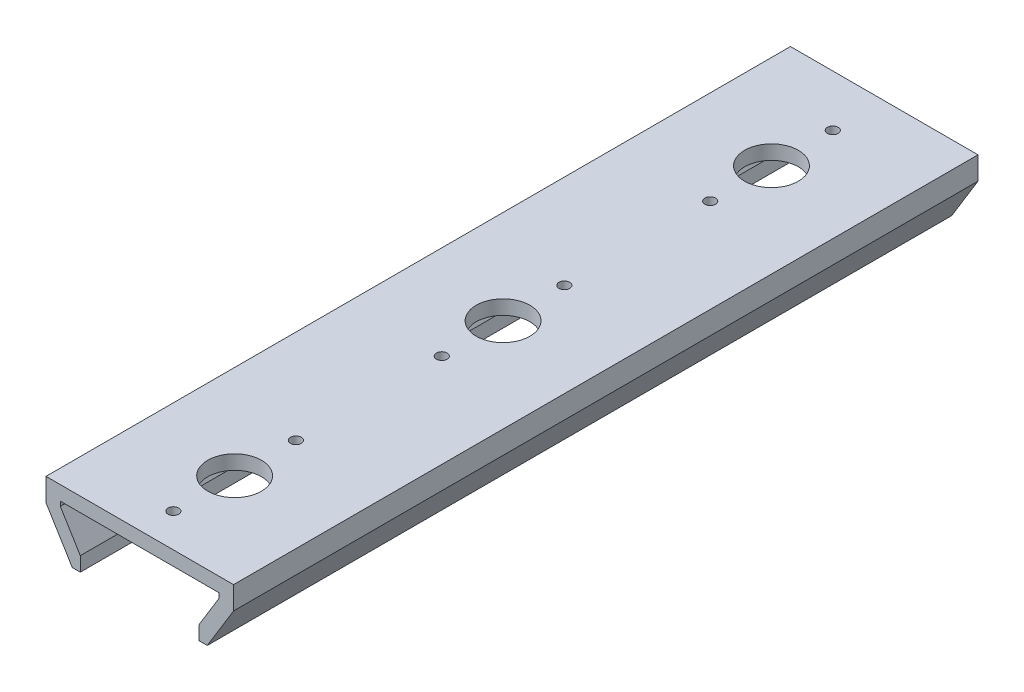
SolidWorks part; units mm, degrees
ref_plane "Płaszczyzna przednia" through (0, 0, 0) normal (0, 0, 1) x (1, 0, 0)
ref_plane "Płaszczyzna górna" through (0, 0, 0) normal (0, 1, 0) x (1, 0, 0)
ref_plane "Płaszczyzna prawa" through (0, 0, 0) normal (1, 0, 0) x (0, 0, -1)
sketch "Sketch1" plane through (0, 0, 0) normal (0, 0, 1) x (1, 0, 0)
  line L0 (0, -13.2894) -> (0, -81.2091) construction
  line L1 (0, -13.4894) -> (22, -13.4894)
  line L2 (22, -13.4894) -> (22, -14.4894)
  line L3 (16.5, -23.4894) -> (0, -23.4894)
  line L4 (22, -14.4894) -> (16.5, -23.4894)
  line L5 (0, -13.4894) -> (0, -23.4894)
  line L6 (0, -13.2894) -> (22.2, -13.2894)
  line L7 (22.2, -13.2894) -> (22.2, -14.5456)
  line L8 (22.2, -14.5456) -> (16.6122, -23.6894)
  line L9 (16.6122, -23.6894) -> (0, -23.6894)
  line L11 (18.8555, -27.6894) -> (16.6122, -27.6894)
  line L13 (-26.2, -9.2894) -> (26.2, -9.2894)
  line L14 (26.2, -9.2894) -> (26.2, -15.6711)
  line L15 (26.2, -15.6711) -> (18.8555, -27.6894)
  line L16 (0, -13.2894) -> (0, -31.461)
  line L17 (16.6122, -23.6894) -> (16.6122, -27.6894)
  line L18 (-4.2, -9.2894) -> (-4.2, -27.6894) construction
  line L20 (-4.2, -9.2894) -> (26.2, -9.2894) construction
  line L21 (18.8555, -27.6894) -> (-4.2, -27.6894) construction
  line L22 (-0.2, -13.2894) -> (-0.2, -23.6894) construction
  line L23 (16.6122, -23.6894) -> (-0.2, -23.6894) construction
  line L24 (-0.2, -13.2894) -> (22.2, -13.2894) construction
  line L25 (-26.2, -9.2894) -> (-26.2, -15.6711)
  line L26 (-26.2, -15.6711) -> (-18.8555, -27.6894)
  line L27 (-18.8555, -27.6894) -> (-16.6122, -27.6894)
  line L28 (-16.6122, -23.6894) -> (-16.6122, -27.6894)
  line L29 (-22.2, -14.5456) -> (-16.6122, -23.6894)
  line L30 (-22.2, -13.2894) -> (-22.2, -14.5456)
  line L31 (0, -13.2894) -> (-22.2, -13.2894)
  point P4 (22, -23.4894)
  dimension "D1" = 9
  dimension "D2" = 5.5
  dimension "D3" = 10
  dimension "D4" = 22
  dimension "D5" = 0.2
  dimension "D6" = 4
extrude "Boss-Extrude1" add sketch "Sketch1" along normal blind 213 contours L31 L6 L7 L8 L17 L11 L15 L14 L13 L25 L26 L27 L28 L29 L30
sketch "Sketch2" plane through (0, -9.2894, 0) normal (0, 1, 0) x (1, 0, 0)
  line L0 (0, 0) -> (0, -186.0262) construction
  circle A0 centre (0, -31.5) radius 7.5
  circle A1 centre (0, -106.5) radius 7.5
  circle A2 centre (0, -181.5) radius 7.5
  dimension "D2" = 15
  dimension "D1" = 186.0262
  dimension "D3" = 31.5
  dimension "D5" = 75
  dimension "D4" = 3
extrude "Cut-Extrude1" cut sketch "Sketch2" against normal blind 213
sketch "Sketch7" plane through (0, -9.2894, 0) normal (0, 1, 0) x (1, 0, 0)
  line L0 (0, -160.3757) -> (0, -189.9157) construction
  line L1 (-0.5, -160.3757) -> (0.5, -160.3757)
  line L2 (-4.5, -164.3757) -> (-4.5, -170.3757)
  line L3 (-4.5, -170.3757) -> (4.5, -170.3757)
  line L4 (4.5, -164.3757) -> (4.5, -170.3757)
  line L5 (-4.5, -160.3757) -> (4.5, -170.3757) construction
  line L6 (-4.5, -170.3757) -> (4.5, -160.3757) construction
  line L7 (-81.2349, -181.5) -> (81.2349, -181.5) construction
  circle A0 centre (0, -181.5) radius 12
  circle A1 centre (0, -181.5) radius 7.5 construction
  circle A2 centre (0, -164.3757) radius 1.5
  arc A3 (0.5, -160.3757) -> (4.5, -164.3757) centre (0.5, -164.3757) cw
  arc A4 (-0.5, -160.3757) -> (-4.5, -164.3757) centre (-0.5, -164.3757) ccw
  circle A5 centre (0, -198.6243) radius 1.5
  point P4 (-80.2434, -146.7844)
  dimension "D1" = 24
  dimension "D4" = 3
  dimension "D6" = 4
  dimension "D2" = 10
  dimension "D3" = 9
  dimension "D5" = 4
extrude "Cut-Extrude2" cut sketch "Sketch7" against normal blind 10 contours A5 | A2
pattern_linear "LPattern1" count 3 spacing 75 along (0, 0, -1) of "Cut-Extrude2"
sketch "Sketch3" plane through (0, -9.2894, 0) normal (0, 1, 0) x (1, 0, 0)
  line L0 (-5, -36.5) -> (5, -26.5) construction
  line L1 (-5, -26.5) -> (5, -26.5)
  line L2 (-5, -26.5) -> (-5, -36.5)
  line L3 (-5, -36.5) -> (5, -36.5)
  line L4 (5, -26.5) -> (5, -36.5)
  circle A0 centre (0, -31.5) radius 7.5
  circle A1 centre (0, -31.5) radius 7.5 construction
  dimension "D1" = 10
  dimension "D2" = 10
ref_plane "Plane1" through (0, 0.7106, 0) normal (0, 1, 0) x (1, 0, 0)
sketch "Sketch5" plane through (0, 0.7106, 0) normal (0, 1, 0) x (1, 0, 0)
  line L1 (-5, -26.5) -> (5, -26.5)
  line L2 (-5, -26.5) -> (-5, -36.5)
  line L3 (-5, -36.5) -> (5, -36.5)
  line L4 (5, -26.5) -> (5, -36.5)
  dimension "D1" = 10
  dimension "D2" = 10
sketch "Szkic1" plane through (0, -9.2894, 0) normal (0, 1, 0) x (1, 0, 0)
  line L0 (26.2, -213) -> (26.2, 0) construction
  line L1 (-26.2, -213) -> (26.2, -213)
  line L2 (-26.2, -213) -> (-26.2, -208)
  line L3 (-26.2, -208) -> (26.2, -208)
  line L4 (26.2, -213) -> (26.2, -208)
  dimension "D1" = 5
extrude "Wytnij-wyciągnięcie1" cut sketch "Szkic1" against normal blind 30.5
